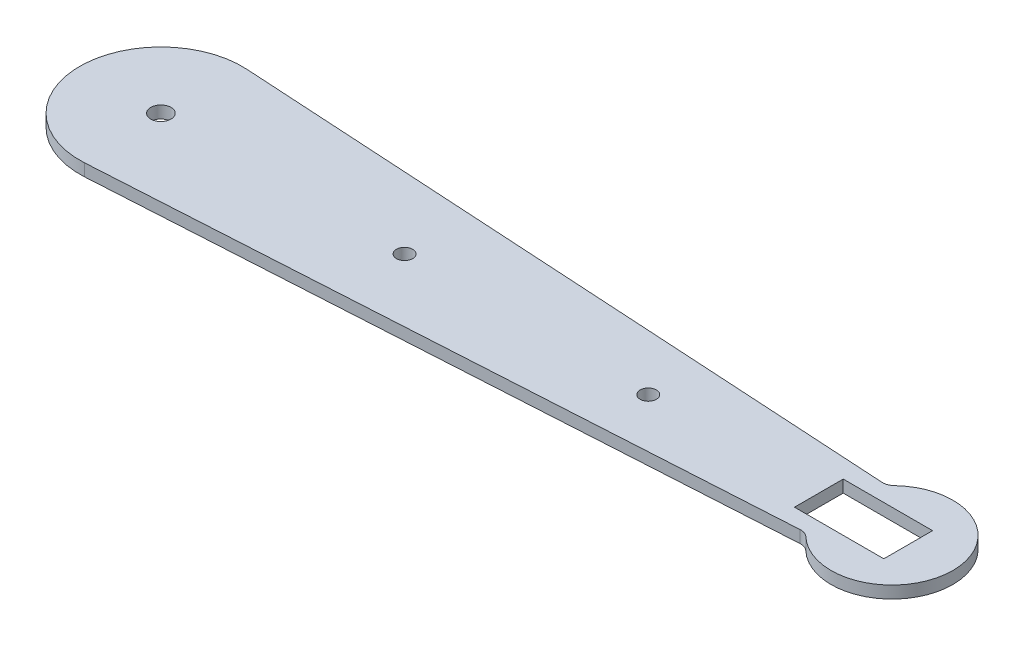
SolidWorks part; units mm, degrees
ref_plane "Front Plane" through (0, 0, 0) normal (0, 0, 1) x (1, 0, 0)
ref_plane "Top Plane" through (0, 0, 0) normal (0, 1, 0) x (1, 0, 0)
ref_plane "Right Plane" through (0, 0, 0) normal (1, 0, 0) x (0, 0, -1)
sketch "Sketch1" plane through (0, 0, 0) normal (0, 1, 0) x (1, 0, 0)
  line L0 (0, 0) -> (180, 0) construction
  line L1 (168.8197, 10) -> (1.1868, 19.9648)
  line L2 (168.8197, -10) -> (1.1868, -19.9648)
  circle A0 centre (0, 0) radius 20
  circle A1 centre (180, 0) radius 15
  circle A2 centre (0, 0) radius 2.5
  circle A4 centre (60, 0) radius 2
  circle A5 centre (120, 0) radius 2
  dimension "D1" = 40
  dimension "D2" = 30
  dimension "D6" = 60
  dimension "D8" = 5
  dimension "D9" = 4
  dimension "D10" = 4
  dimension "D3" = 180
  dimension "D4" = 10
  dimension "D5" = 10
  dimension "D7" = 120
extrude "Boss-Extrude1" add sketch "Sketch1" along normal blind 3
fillet "Fillet2" radius 3 1 edges at (168.8197, 1.5, -10)
fillet "Fillet3" radius 3 1 edges at (168.8197, 1.5, 10)
sketch "Sketch2" plane through (0, 3, 0) normal (0, 1, 0) x (1, 0, 0)
  line L1 (162, 6) -> (184, 6)
  line L2 (162, 6) -> (162, -6)
  line L3 (162, -6) -> (184, -6)
  line L4 (184, 6) -> (184, -6)
  arc A0 (169.6916, -10.8967) -> (169.6916, 10.8967) centre (180, 0) ccw construction
  point P7 (195, 0)
  dimension "D1" = 12
  dimension "D2" = 22
  dimension "D3" = 6
  dimension "D5" = 4
extrude "Cut-Extrude1" cut sketch "Sketch2" against normal blind 10
